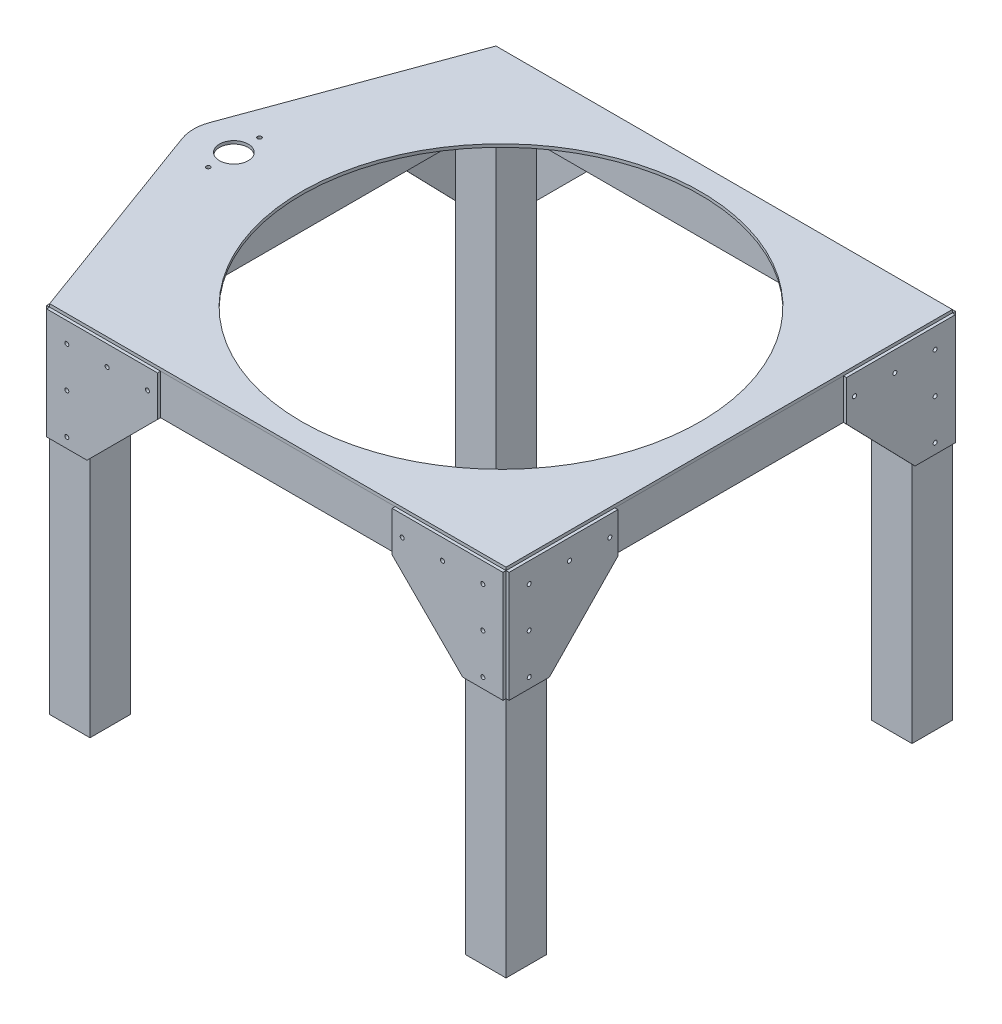
SolidWorks part; units mm, degrees
ref_plane "Front Plane" through (0, 0, 0) normal (0, 0, 1) x (1, 0, 0)
ref_plane "Top Plane" through (0, 0, 0) normal (0, 1, 0) x (1, 0, 0)
ref_plane "Right Plane" through (0, 0, 0) normal (1, 0, 0) x (0, 0, -1)
sketch "Sketch1" plane through (0, 0, 0) normal (0, 1, 0) x (1, 0, 0)
  line B0 (-15, -100) -> (-15, 100) construction
  line B1 (-185.65, 100) -> (-165.65, 100)
  line B2 (-185.65, 100) -> (-185.65, -100)
  line B3 (-185.65, -100) -> (-165.65, -100)
  line B4 (155.65, 100) -> (155.65, -100)
  line B5 (-165.65, 100) -> (-165.65, -100)
  line B6 (135.65, -100) -> (135.65, 100)
  line B7 (135.65, 100) -> (155.65, 100)
  line B8 (-250, 7.3323) -> (-251, 6.755) construction
  line B9 (-251.7321, 6.3323) -> (-254.6179, 4.6662)
  line B10 (-256.35, 1.6662) -> (-256.35, -1.6662)
  line B11 (-254.6179, -4.6662) -> (-251.7321, -6.3323)
  line B12 (-248.2679, -6.3323) -> (-245.3821, -4.6662)
  line B13 (-243.65, -1.6662) -> (-243.65, 1.6662)
  line B14 (-245.3821, 4.6662) -> (-248.2679, 6.3323)
  line B15 (-251, 6.755) -> (-251.7321, 6.3323) construction
  line B16 (-256.35, 3.6662) -> (-256.35, 1.6662) construction
  line B17 (-254.6179, 4.6662) -> (-256.35, 3.6662) construction
  line B18 (-256.35, -1.6662) -> (-256.35, -3.6662) construction
  line B19 (-256.35, -3.6662) -> (-254.6179, -4.6662) construction
  line B20 (-251.7321, -6.3323) -> (-250, -7.3323) construction
  line B21 (-250, -7.3323) -> (-248.2679, -6.3323) construction
  line B22 (-245.3821, -4.6662) -> (-243.65, -3.6662) construction
  line B23 (-243.65, 3.6662) -> (-245.3821, 4.6662) construction
  line B24 (-243.65, 1.6662) -> (-243.65, 3.6662) construction
  line B25 (-272.29, 225) -> (272.29, 225)
  line B26 (-272.29, 225) -> (-272.29, -225)
  line B27 (-272.29, -225) -> (272.29, -225)
  line B28 (272.29, 225) -> (272.29, -225)
  line B29 (350, -318.9185) -> (-350, -318.9185) construction
  line B30 (350, -318.9185) -> (350, 481.0815) construction
  line B31 (350, 481.0815) -> (-350, 481.0815) construction
  line B32 (-350, -318.9185) -> (-350, 481.0815) construction
  line B33 (-150.65, -285.4616) -> (-150.65, -318.9185)
  circle B34 centre (0, 0) radius 193.0298 construction
  circle B35 centre (0, 0) radius 120.65
  circle B36 centre (0, 193.0298) radius 6.35
  circle B37 centre (121.4927, 136.4927) radius 6.35
  circle B38 centre (178.0298, 0) radius 6.35
  circle B39 centre (121.4927, -136.4927) radius 6.35
  circle B40 centre (-15, -193.0298) radius 6.35
  circle B41 centre (-151.4927, -136.4927) radius 6.35
  circle B42 centre (-151.4927, -136.4927) radius 4.7625
  circle B43 centre (-151.4927, -136.4927) radius 3.175
  circle B44 centre (-193.0298, 0) radius 6.35
  circle B45 centre (-193.0298, 0) radius 4.7625
  circle B46 centre (-193.0298, 0) radius 18.175
  circle B47 centre (-136.4927, 136.4927) radius 6.35
  circle B48 centre (-136.4927, 136.4927) radius 4.7625
  circle B49 centre (-136.4927, 136.4927) radius 3.175
  circle B50 centre (-175.65, 95) radius 2
  circle B51 centre (-175.65, 67.8571) radius 2
  circle B52 centre (-175.65, 40.7143) radius 2
  circle B53 centre (-175.65, 13.5714) radius 2
  circle B54 centre (-175.65, -13.5714) radius 2
  circle B55 centre (-175.65, -40.7143) radius 2
  circle B56 centre (-175.65, -67.8571) radius 2
  circle B57 centre (-175.65, -95) radius 2
  circle B58 centre (0, 0) radius 225 construction
  circle B59 centre (-250, 0) radius 25 construction
  circle B60 centre (-250, 0) radius 6.35 construction
  circle B61 centre (-250, 5.0229) radius 2 construction
  circle B62 centre (-250, 5.3323) radius 2 construction
  arc B63 (-251.7321, 6.3323) -> (-248.2679, 6.3323) centre (-250, 5.3323) cw
  arc B64 (-245.3821, 4.6662) -> (-243.65, 1.6662) centre (-245.3821, 2.6662) cw
  arc B65 (-243.65, -1.6662) -> (-245.3821, -4.6662) centre (-245.3821, -2.6662) cw
  arc B66 (-248.2679, -6.3323) -> (-251.7321, -6.3323) centre (-250, -5.3323) cw
  arc B67 (-254.6179, -4.6662) -> (-256.35, -1.6662) centre (-254.6179, -2.6662) cw
  arc B68 (-256.35, 1.6662) -> (-254.6179, 4.6662) centre (-254.6179, 2.6662) cw
  circle B69 centre (-250, 0) radius 14.29
  circle B70 centre (-250, 0) radius 25.4 construction
  circle B71 centre (-250, 25.4) radius 2
  circle B72 centre (-250, -25.4) radius 2
sketch_block_instance "static plate shooter-1"
sketch_block "static plate shooter" parameters "D2"=241.3, "D3"=12.7, "D4"=9.525, "D5"=6.35, "D6"=4, "D9"=50, "D10"=12.7, "D11"=4, "D12"=450, "D14"=28.58, "D18"=50.8, "D19"=4, "D1"=20, "D7"=3, "D8"=3, "D13"=13.7952, "D15"=8, "D16"=700, "D17"=800
sketch "Sketch4" plane through (0, 0, 0) normal (0, 1, 0) x (1, 0, 0)
  line L0 (0, 0) -> (-272.29, 225) construction
  line L1 (-186.3798, 181.3798) -> (-186.3798, 221.3798)
  line L2 (-186.3798, 181.3798) -> (-226.3798, 181.3798)
  line L3 (-226.3798, 181.3798) -> (-226.3798, 221.3798)
  line L4 (-186.3798, 221.3798) -> (-226.3798, 221.3798)
  line L5 (0, -440) -> (0, 440) construction
  line L6 (186.3798, 181.3798) -> (226.3798, 181.3798)
  line L7 (186.3798, 181.3798) -> (186.3798, 221.3798)
  line L8 (226.3798, 181.3798) -> (226.3798, 221.3798)
  line L9 (186.3798, 221.3798) -> (226.3798, 221.3798)
  line L10 (-393.25, 0) -> (393.25, 0) construction
  line L11 (186.3798, -221.3798) -> (226.3798, -221.3798)
  line L12 (226.3798, -181.3798) -> (226.3798, -221.3798)
  line L13 (186.3798, -181.3798) -> (186.3798, -221.3798)
  line L14 (186.3798, -181.3798) -> (226.3798, -181.3798)
  line L15 (-186.3798, -221.3798) -> (-226.3798, -221.3798)
  line L16 (-226.3798, -181.3798) -> (-226.3798, -221.3798)
  line L17 (-186.3798, -181.3798) -> (-226.3798, -181.3798)
  line L18 (-186.3798, -181.3798) -> (-186.3798, -221.3798)
  line L19 (-300.921, 0) -> (-265, 35.921)
  line L20 (-186.3798, -221.3798) -> (186.3798, -221.3798)
  line L24 (-186.3798, -221.3798) -> (186.3798, -221.3798)
  line L26 (-186.3798, -221.3798) -> (-186.3798, -181.3798)
  line L28 (-186.3798, -181.3798) -> (-186.3798, -221.3798)
  line L31 (-186.3798, -181.3798) -> (186.3798, -181.3798)
  line L32 (-186.3798, -201.3798) -> (186.3798, -201.3798) construction
  line L33 (-15, -100) -> (-15, 100) construction
  line L34 (-300.921, 0) -> (-265, -35.921)
  line L35 (-265, 35.921) -> (-229.079, 0)
  line L36 (-302.552, 13.7784) -> (-226.3798, 221.3798)
  line L37 (-302.552, -13.7784) -> (-226.3798, -221.3798)
  line L38 (186.3798, -221.3798) -> (186.3798, -181.3798)
  line L39 (-265, -35.921) -> (-229.079, 0)
  line L40 (-300.921, 0) -> (-229.079, 0) construction
  line L41 (186.3798, 181.3798) -> (226.3798, 181.3798)
  line L42 (-265, 35.921) -> (-265, -35.921) construction
  line L45 (186.3798, 181.3798) -> (186.3798, -181.3798)
  line L47 (-186.3798, 221.3798) -> (186.3798, 221.3798)
  line L48 (-186.3798, 221.3798) -> (-186.3798, 201.3798)
  line L49 (-186.3798, 201.3798) -> (186.3798, 201.3798)
  line L50 (186.3798, 221.3798) -> (186.3798, 201.3798)
  line L51 (186.3798, -181.3798) -> (226.3798, -181.3798)
  line L52 (226.3798, 181.3798) -> (226.3798, -181.3798)
  line L53 (-226.3798, 181.3798) -> (-186.3798, 181.3798)
  line L54 (-226.3798, 181.3798) -> (-226.3798, -181.3798)
  line L55 (-226.3798, -181.3798) -> (-186.3798, -181.3798)
  line L56 (-186.3798, 181.3798) -> (-186.3798, -181.3798)
  circle A2 centre (-265, 0) radius 40 construction
  circle A8 centre (0, 0) radius 197.7923
  circle A9 centre (-136.4927, 136.4927) radius 4.7625 construction
  circle A10 centre (-193.0298, 0) radius 4.7625 construction
  circle A11 centre (178.0298, 0) radius 6.35 construction
  circle A18 centre (-265, 0) radius 14.29
  circle A24 centre (0, 193.0298) radius 6.35 construction
  circle A25 centre (-15, 398.0877) radius 120.65 construction
  circle A27 centre (-265, 0) radius 25.4 construction
  circle A28 centre (0, 0) radius 225 construction
  circle A29 centre (0, 0) radius 225 construction
  arc A31 (-302.552, 13.7784) -> (-302.552, -13.7784) centre (-265, 0) ccw
  circle A33 centre (-265, 25.4) radius 2
  circle A34 centre (-265, -25.4) radius 2
  dimension "D3" = 80
  dimension "D4" = 28.58
  dimension "D6" = 4
  dimension "D7" = 2
  dimension "D10" = 2
  dimension "D11" = 241.3
  dimension "D5" = 50.8
  dimension "D1" = 40
  dimension "D2" = 40
  dimension "D9" = 20
sketch "Sketch5" plane through (0, 0, 0) normal (0, 1, 0) x (1, 0, 0)
  line L0 (186.3798, -221.3798) -> (226.3798, -221.3798) construction
  line L2 (226.3798, 181.3798) -> (226.3798, 221.3798) construction
  line L4 (186.3798, 221.3798) -> (226.3798, 221.3798) construction
  line L6 (-186.3798, 221.3798) -> (-226.3798, 221.3798) construction
  line L8 (226.3798, 181.3798) -> (226.3798, 221.3798)
  line L9 (226.3798, 181.3798) -> (226.3798, -181.3798) construction
  line L10 (226.3798, 181.3798) -> (226.3798, -181.3798)
  line L11 (226.3798, -181.3798) -> (226.3798, -221.3798) construction
  line L12 (-186.3798, -221.3798) -> (186.3798, -221.3798) construction
  line L14 (-186.3798, -221.3798) -> (-226.3798, -221.3798) construction
  line L15 (186.3798, -221.3798) -> (226.3798, -221.3798)
  line L19 (186.3798, 221.3798) -> (226.3798, 221.3798)
  line L21 (-186.3798, 221.3798) -> (-226.3798, 221.3798)
  line L27 (-186.3798, -221.3798) -> (186.3798, -221.3798)
  line L29 (-186.3798, -221.3798) -> (-226.3798, -221.3798)
  line L30 (226.3798, -181.3798) -> (226.3798, -221.3798)
  line L31 (-256.35, 1.6662) -> (-256.35, -1.6662) construction
  line L32 (-302.552, 13.7784) -> (-226.3798, 221.3798) construction
  line L33 (-302.552, -13.7784) -> (-226.3798, -221.3798) construction
  line L34 (-302.552, 13.7784) -> (-226.3798, 221.3798)
  line L35 (-302.552, -13.7784) -> (-226.3798, -221.3798)
  line L36 (-186.3798, 221.3798) -> (186.3798, 221.3798)
  line L43 (-254.6179, -4.6662) -> (-251.7321, -6.3323) construction
  line L44 (-248.2679, -6.3323) -> (-245.3821, -4.6662) construction
  line L45 (-243.65, -1.6662) -> (-243.65, 1.6662) construction
  line L46 (-245.3821, 4.6662) -> (-248.2679, 6.3323) construction
  line L47 (-251.7321, 6.3323) -> (-254.6179, 4.6662) construction
  line L48 (-256.35, 1.6662) -> (-256.35, -1.6662) construction
  line L49 (-254.6179, -4.6662) -> (-251.7321, -6.3323) construction
  line L50 (-248.2679, -6.3323) -> (-245.3821, -4.6662) construction
  line L51 (-243.65, -1.6662) -> (-243.65, 1.6662) construction
  line L52 (-245.3821, 4.6662) -> (-248.2679, 6.3323) construction
  line L53 (-251.7321, 6.3323) -> (-254.6179, 4.6662) construction
  line L54 (-250, 5.3323) -> (-250, -5.3323) construction
  line L55 (-265, 0) -> (-245.3821, 0) construction
  line L56 (-271.35, 1.6662) -> (-271.35, -1.6662)
  line L57 (-269.6179, -4.6662) -> (-266.7321, -6.3323)
  line L58 (-263.2679, -6.3323) -> (-260.3821, -4.6662)
  line L59 (-258.65, -1.6662) -> (-258.65, 1.6662)
  line L60 (-260.3821, 4.6662) -> (-263.2679, 6.3323)
  line L61 (-266.7321, 6.3323) -> (-269.6179, 4.6662)
  line L64 (-269.6179, 4.6662) -> (-265, 0) construction
  line L65 (-265, 0) -> (-266.7321, 6.3323) construction
  line L66 (-271.35, 1.6662) -> (-265, 0) construction
  line L67 (-265, 0) -> (-271.35, -1.6662) construction
  line L68 (-269.6179, -4.6662) -> (-265, 0) construction
  line L69 (-265, 0) -> (-266.7321, -6.3323) construction
  line L70 (-263.2679, -6.3323) -> (-265, 0) construction
  line L71 (-265, 0) -> (-260.3821, -4.6662) construction
  line L72 (-258.65, -1.6662) -> (-265, 0) construction
  line L73 (-265, 0) -> (-258.65, 1.6662) construction
  line L74 (-263.2679, 6.3323) -> (-265, 0) construction
  line L75 (-265, 0) -> (-260.3821, 4.6662) construction
  arc A0 (-271.35, -1.6662) -> (-269.6179, -4.6662) centre (-269.6179, -2.6662) ccw
  arc A2 (-302.552, 13.7784) -> (-302.552, -13.7784) centre (-265, 0) ccw construction
  arc A5 (-266.7321, -6.3323) -> (-263.2679, -6.3323) centre (-265, -5.3323) ccw
  arc A6 (-260.3821, -4.6662) -> (-258.65, -1.6662) centre (-260.3821, -2.6662) ccw
  arc A7 (-258.65, 1.6662) -> (-260.3821, 4.6662) centre (-260.3821, 2.6662) ccw
  arc A8 (-263.2679, 6.3323) -> (-266.7321, 6.3323) centre (-265, 5.3323) ccw
  arc A9 (-269.6179, 4.6662) -> (-271.35, 1.6662) centre (-269.6179, 2.6662) ccw
  circle A10 centre (-265, -25.4) radius 2 construction
  circle A11 centre (-265, 25.4) radius 2 construction
  circle A12 centre (-265, -25.4) radius 2
  circle A13 centre (-265, 25.4) radius 2
  circle A14 centre (0, 0) radius 197.7923 construction
  circle A15 centre (0, 0) radius 197.7923
  arc A31 (-302.552, 13.7784) -> (-302.552, -13.7784) centre (-265, 0) ccw
  circle A32 centre (-265, 0) radius 14.29 construction
  circle A33 centre (-265, 0) radius 14.29
  arc A34 (-256.35, -1.6662) -> (-254.6179, -4.6662) centre (-254.6179, -2.6662) ccw construction
  arc A35 (-251.7321, -6.3323) -> (-248.2679, -6.3323) centre (-250, -5.3323) ccw construction
  arc A36 (-245.3821, -4.6662) -> (-243.65, -1.6662) centre (-245.3821, -2.6662) ccw construction
  arc A37 (-243.65, 1.6662) -> (-245.3821, 4.6662) centre (-245.3821, 2.6662) ccw construction
  arc A38 (-248.2679, 6.3323) -> (-251.7321, 6.3323) centre (-250, 5.3323) ccw construction
  arc A39 (-254.6179, 4.6662) -> (-256.35, 1.6662) centre (-254.6179, 2.6662) ccw construction
  arc A40 (-256.35, -1.6662) -> (-254.6179, -4.6662) centre (-254.6179, -2.6662) ccw construction
  arc A41 (-251.7321, -6.3323) -> (-248.2679, -6.3323) centre (-250, -5.3323) ccw construction
  arc A42 (-245.3821, -4.6662) -> (-243.65, -1.6662) centre (-245.3821, -2.6662) ccw construction
  arc A43 (-243.65, 1.6662) -> (-245.3821, 4.6662) centre (-245.3821, 2.6662) ccw construction
  arc A44 (-248.2679, 6.3323) -> (-251.7321, 6.3323) centre (-250, 5.3323) ccw construction
  arc A45 (-254.6179, 4.6662) -> (-256.35, 1.6662) centre (-254.6179, 2.6662) ccw construction
  point P23 (-250, 0)
  point P46 (-265, 0)
  dimension "D1" = 12.7
extrude "Boss-Extrude1" add sketch "Sketch5" along normal blind 3 contours L34 A31 L35 L29 L27 L15 L30 L10 L8 L19 L36 L21 A33 A12 A13 A15
sketch "Sketch6" plane through (0, 0, 0) normal (0, -1, 0) x (1, 0, 0)
  line L8 (186.3798, 181.3798) -> (186.3798, 221.3798) construction
  line L9 (186.3798, 181.3798) -> (226.3798, 181.3798) construction
  line L10 (226.3798, 181.3798) -> (226.3798, 221.3798) construction
  line L11 (186.3798, 221.3798) -> (226.3798, 221.3798) construction
  line L12 (186.3798, 181.3798) -> (186.3798, 221.3798)
  line L13 (186.3798, 181.3798) -> (226.3798, 181.3798)
  line L14 (226.3798, 181.3798) -> (226.3798, 221.3798)
  line L15 (186.3798, 221.3798) -> (226.3798, 221.3798)
  line L32 (188.3798, 183.3798) -> (188.3798, 219.3798)
  line L33 (188.3798, 183.3798) -> (224.3798, 183.3798)
  line L34 (188.3798, 219.3798) -> (224.3798, 219.3798)
  line L35 (224.3798, 183.3798) -> (224.3798, 219.3798)
  line L36 (188.3798, 183.3798) -> (224.3798, 219.3798) construction
  line L37 (188.3798, 219.3798) -> (224.3798, 183.3798) construction
  point P15 (206.3798, 219.3798)
  point P17 (206.3798, 201.3798)
  point P18 (206.3798, 221.3798)
  point P19 (224.3798, 201.3798)
  point P24 (226.3798, 201.3798)
  line M11 (226.3798, -221.3798) -> (226.3798, 221.3798)
  line M12 (226.3798, 221.3798) -> (-226.3798, 221.3798)
  dimension "D1" = 2
  dimension "D2" = 2
extrude "Boss-Extrude2" add sketch "Sketch6" along normal blind 350 separate body contours L12 L13 L35 L33 L32 L34 M11 M12
mirror "Mirror2" about plane through (0, 0, 0) normal (1, 0, 0) of bodies 102
mirror "Mirror3" about plane through (0, 0, 0) normal (0, 0, 1) of bodies 102 103
sketch "Sketch8" plane through (186.3798, 0, 0) normal (-1, 0, 0) x (0, 0, 1)
  line L0 (-221.3798, 0) -> (-201.3798, -40) construction
  line L1 (-221.3798, 0) -> (-201.3798, 0)
  line L2 (-221.3798, 0) -> (-221.3798, -40)
  line L3 (-221.3798, -40) -> (-201.3798, -40)
  line L4 (-201.3798, 0) -> (-201.3798, -40)
  line L6 (-203.3798, -38) -> (-219.3798, -38)
  line L7 (-203.3798, -38) -> (-203.3798, -2)
  line L8 (-203.3798, -2) -> (-219.3798, -2)
  line L9 (-219.3798, -38) -> (-219.3798, -2)
  line L10 (-203.3798, -38) -> (-219.3798, -2) construction
  line L11 (-203.3798, -2) -> (-219.3798, -38) construction
  point P4 (-211.3798, -20)
  dimension "D1" = 2
  dimension "D2" = 2
  dimension "D3" = 20
  dimension "D4" = 40
extrude "Boss-Extrude3" add sketch "Sketch8" along normal up to surface (372.7597 mm away) separate body up to face at (-186.3798, -175, 201.3798)
mirror "Mirror4" about plane through (0, 0, 0) normal (0, 0, 1) of bodies 106
sketch "Sketch9" plane through (0, 0, -181.3798) normal (0, 0, 1) x (1, 0, 0)
  line L0 (226.3798, -350) -> (226.3798, 0) construction
  line L1 (206.3798, 0) -> (226.3798, 0)
  line L2 (206.3798, 0) -> (206.3798, -40)
  line L3 (206.3798, -40) -> (226.3798, -40)
  line L4 (226.3798, 0) -> (226.3798, -40)
  line L5 (226.3798, 0) -> (186.3798, 0) construction
  line L6 (208.3798, -2) -> (224.3798, -2)
  line L7 (208.3798, -2) -> (208.3798, -38)
  line L8 (208.3798, -38) -> (224.3798, -38)
  line L9 (224.3798, -2) -> (224.3798, -38)
  point P11 (216.3798, -38)
  point P12 (216.3798, -40)
  point P13 (224.3798, -20)
  point P14 (226.3798, -20)
  line M6 (226.3798, 0) -> (186.3798, 0)
  line M7 (186.3798, 0) -> (186.3798, -350)
  line M9 (226.3798, -350) -> (226.3798, 0)
  dimension "D1" = 40
  dimension "D2" = 2
  dimension "D3" = 2
  dimension "D4" = 20
extrude "Boss-Extrude4" add sketch "Sketch9" along normal up to surface (362.7597 mm away) separate body contours L3 L6 L9 L8 L7 M7 M9 M6 up to face at (206.3798, -175, 181.3798)
mirror "Mirror6" about plane through (0, 0, 0) normal (1, 0, 0) of bodies 108
sketch "Sketch10" plane through (0, 0, -221.3798) normal (0, 0, -1) x (-1, 0, 0)
  line L0 (126.3798, -20) -> (166.3798, -20) construction
  line L1 (166.3798, -20) -> (206.3798, -20) construction
  line L2 (206.3798, -20) -> (206.3798, -60) construction
  line L3 (206.3798, -60) -> (206.3798, -100) construction
  line L4 (186.3798, -40) -> (186.3798, 0) construction
  line L5 (186.3798, 0) -> (186.3798, -350) construction
  line L8 (226.3798, 0) -> (186.3798, 0) construction
  line L9 (186.3798, -350) -> (226.3798, -350) construction
  line L10 (226.3798, -350) -> (226.3798, 0) construction
  line L12 (186.3798, 0) -> (-186.3798, 0) construction
  line L13 (-186.3798, 0) -> (-186.3798, -40) construction
  line L14 (226.3798, 0) -> (186.3798, 0)
  line L15 (186.3798, 0) -> (186.3798, -110)
  line L16 (186.3798, -350) -> (226.3798, -350)
  line L17 (226.3798, -110) -> (226.3798, 0)
  line L19 (186.3798, -40) -> (186.3798, 0)
  line L20 (186.3798, 0) -> (116.3798, 0)
  line L21 (-186.3798, 0) -> (-186.3798, -40)
  line L22 (116.3798, 0) -> (116.3798, -40)
  line L23 (186.3798, -110) -> (226.3798, -110)
  line L24 (116.3798, -40) -> (186.3798, -110)
  circle A0 centre (206.3798, -20) radius 2
  circle A1 centre (206.3798, -60) radius 2
  circle A2 centre (206.3798, -100) radius 2
  circle A3 centre (166.3798, -20) radius 2
  circle A4 centre (126.3798, -20) radius 2
  point P13 (116.3798, -20)
  point P28 (206.3798, 0)
  dimension "D1" = 4
  dimension "D3" = 8
  dimension "D4" = 8
  dimension "D2" = 40
extrude "Boss-Extrude5" add sketch "Sketch10" along normal blind 3 separate body
sketch "Sketch11" plane through (-226.3798, 0, 0) normal (-1, 0, 0) x (0, 0, 1)
  line L2 (-224.3798, -20) -> (-221.3798, -20) construction
  line L3 (-181.3798, 0) -> (-221.3798, 0) construction
  line L4 (-221.3798, 0) -> (-221.3798, -350) construction
  line L5 (-221.3798, -350) -> (-181.3798, -350) construction
  line L6 (-181.3798, -350) -> (-181.3798, 0) construction
  line L7 (181.3798, -40) -> (181.3798, 0) construction
  line L8 (181.3798, 0) -> (-181.3798, 0) construction
  line L9 (-181.3798, 0) -> (-181.3798, -40) construction
  line L10 (-181.3798, -40) -> (181.3798, -40) construction
  line L11 (-181.3798, 0) -> (-221.3798, 0)
  line L12 (-221.3798, 0) -> (-221.3798, -350)
  line L13 (-221.3798, -350) -> (-181.3798, -350)
  line L14 (-181.3798, -350) -> (-181.3798, 0)
  line L15 (181.3798, -40) -> (181.3798, 0)
  line L16 (181.3798, 0) -> (-181.3798, 0)
  line L17 (-181.3798, 0) -> (-181.3798, -40)
  line L18 (-181.3798, -40) -> (181.3798, -40)
  line L19 (-221.3798, -110) -> (-181.3798, -110)
  line L20 (-224.3798, -110) -> (-221.3798, -110) construction
  line L21 (-113.3798, -40) -> (-113.3798, 0)
  line L22 (-181.3798, -110) -> (-113.3798, -40)
  circle A0 centre (-201.3798, -20) radius 2
  circle A2 centre (-161.3798, -20) radius 2
  circle A3 centre (-121.3798, -20) radius 2
  circle A4 centre (-201.3798, -60) radius 2
  circle A5 centre (-201.3798, -100) radius 2
  line M6 (-181.3798, 0) -> (-221.3798, 0)
  line M7 (-221.3798, 0) -> (-221.3798, -350)
  dimension "D5" = 4
  dimension "D3" = 40
  dimension "D4" = 40
  dimension "D6" = 8
  dimension "D7" = 40
  dimension "D8" = 20
  dimension "D1" = 3
  dimension "D2" = 3
extrude "Boss-Extrude6" add sketch "Sketch11" along normal blind 3 separate body contours L19 L22 L14 A5 A4 A0 M6 M7 | L14 L22 L18 | L18 L22 L21 L16 L14 A3 A2
mirror "Mirror7" about plane through (0, 0, 0) normal (0, 0, 1) of bodies 111
mirror "Mirror8" about plane through (0, 0, 0) normal (1, 0, 0) of bodies 111 112
mirror "Mirror9" about plane through (0, 0, 0) normal (1, 0, 0) of bodies 110
mirror "Mirror10" about plane through (0, 0, 0) normal (0, 0, 1) of bodies 115 110
